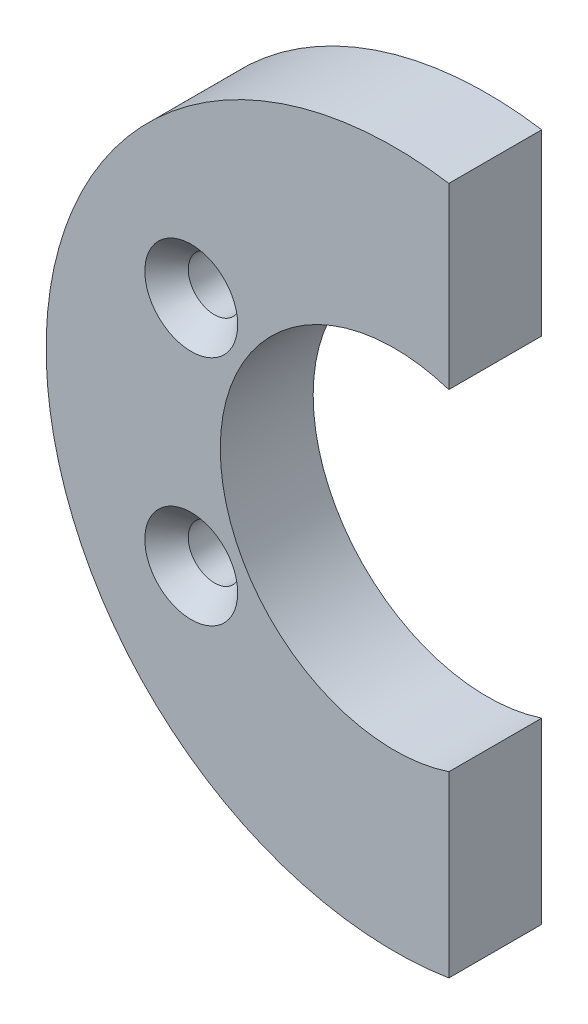
SolidWorks part; units mm, degrees
ref_plane "Front Plane" through (0, 0, 0) normal (0, 0, 1) x (1, 0, 0)
ref_plane "Top Plane" through (0, 0, 0) normal (0, 1, 0) x (1, 0, 0)
ref_plane "Right Plane" through (0, 0, 0) normal (1, 0, 0) x (0, 0, -1)
sketch "Sketch2" plane through (0, 0, 0) normal (0, 0, 1) x (1, 0, 0)
  line L0 (2.9736, 18.8165) -> (2.9736, 9.0489)
  line L1 (2.9736, -9.0489) -> (2.9736, -18.8165)
  arc A0 (2.9736, 9.0489) -> (2.9736, -9.0489) centre (0, 0) ccw
  arc A1 (2.9736, 18.8165) -> (2.9736, -18.8165) centre (0, 0) ccw
extrude "Boss-Extrude1" add sketch "Sketch2" along normal blind 5.08
sketch "Sketch3" plane through (0, 0, 5.08) normal (0, 0, 1) x (1, 0, 0)
  line L0 (0, 0) -> (-23.1797, 0) construction
  line L1 (-11.1125, -6.35) -> (-11.1125, 6.35) construction
  point P6 (-11.1125, 0)
  dimension "D1" = 11.1125
  dimension "D2" = 12.7
hole_wizard "CSK for #10 Flat Head Machine Screw (100)1" positions "3DSketch2" profile "Sketch4" countersink size "#10" standard "ANSI Inch" end condition through all
sketch3d "3DSketch2"
  point P0 (-11.1125, 6.35, 5.08)
  point P3 (-11.1125, -6.35, 5.08)
sketch "Sketch4" plane through (-11.1125, 6.35, 5.08) normal (1, 0, 0) x (0, -1, 0)
  line L0 (0, 0) -> (0, 5.08)
  line L1 (0, 5.08) -> (1.4351, 5.08)
  line L2 (1.4351, 5.08) -> (1.4351, 1.271)
  line L3 (1.4351, 1.271) -> (2.54, 0)
  line L5 (2.54, 0) -> (0, 0)
  line L6 (-1.4351, 1.271) -> (-2.54, 0) construction
  line L11 (0, -6.35) -> (0, 107.95) construction
  dimension "Thru Hole Dia." = 2.8702
  dimension "Thru Hole Depth" = 5.08
  dimension "Near C'Sink Dia." = 5.08
  dimension "Near C'Sink Angle" = 82
